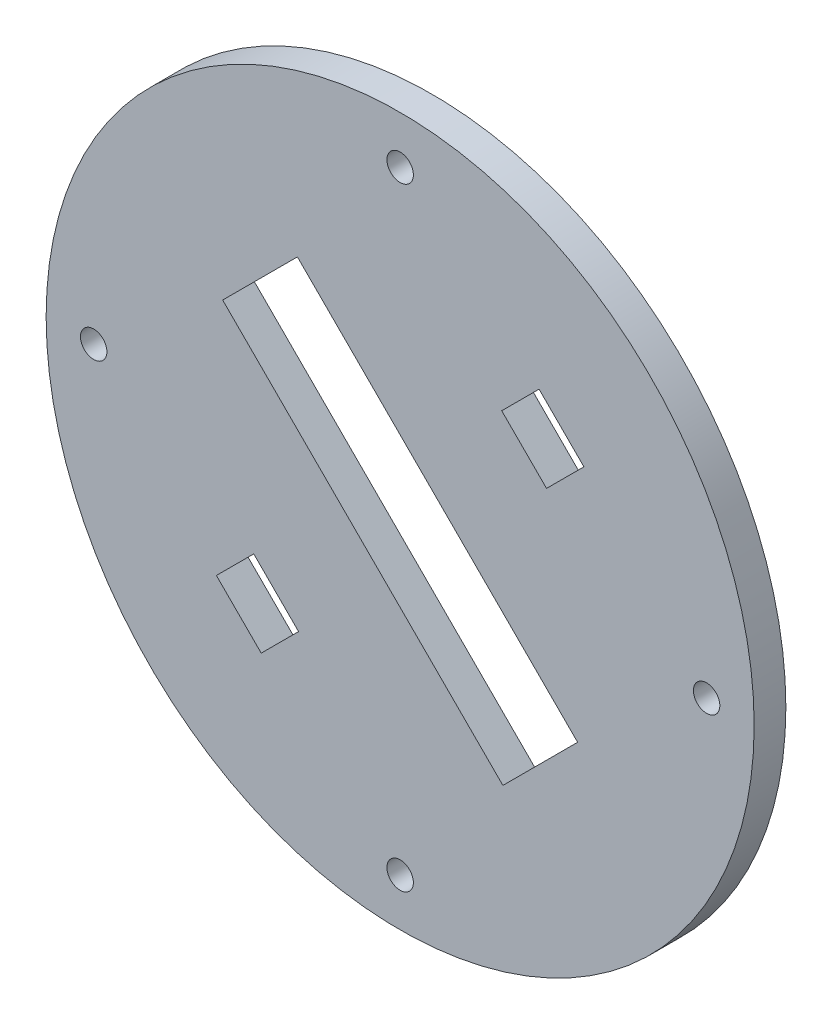
SolidWorks part; units mm, degrees
ref_plane "Front Plane" through (0, 0, 0) normal (0, 0, 1) x (1, 0, 0)
ref_plane "Top Plane" through (0, 0, 0) normal (0, 1, 0) x (1, 0, 0)
ref_plane "Right Plane" through (0, 0, 0) normal (1, 0, 0) x (0, 0, -1)
sketch "Sketch1" plane through (0, 0, 0) normal (0, 0, 1) x (1, 0, 0)
  circle A0 centre (0, 0) radius 67
  circle A1 centre (0, 58) radius 2.5
  circle A2 centre (58, 0) radius 2.5
  circle A3 centre (0, -58) radius 2.5
  circle A4 centre (-58, 0) radius 2.5
  point P14 (0, 0)
  dimension "D1" = 4
  dimension "D2" = 58
extrude "Boss-Extrude1" add sketch "Sketch1" along normal blind 6
sketch "Sketch2" plane through (0, 0, 6) normal (0, 0, 1) x (1, 0, 0)
  circle A0 centre (-42.4264, -42.4264) radius 1.5
  circle A1 centre (42.4264, 42.4264) radius 1.5
  circle A2 centre (-38.8909, 38.8909) radius 1.5
  circle A3 centre (38.8909, -38.8909) radius 1.5
  point P8 (0, 0)
  point P9 (0, 0)
  point P10 (0, 0)
  dimension "D1" = 3
  dimension "D2" = 3
  dimension "D3" = 55
  dimension "D4" = 60
  dimension "D5" = 60
sketch "Sketch3" plane through (0, 0, 6) normal (0, 0, 1) x (1, 0, 0)
  line L0 (-38.8909, 38.8909) -> (38.8909, -38.8909) construction
  line L1 (-34.4246, -26.6464) -> (-27.3536, -19.5754)
  line L2 (-34.4246, -26.6464) -> (-26.6464, -34.4246)
  line L3 (-26.6464, -34.4246) -> (-19.5754, -27.3536)
  line L4 (-27.3536, -19.5754) -> (-19.5754, -27.3536)
  line L5 (-34.4246, -26.6464) -> (-19.5754, -27.3536) construction
  line L6 (-26.6464, -34.4246) -> (-27.3536, -19.5754) construction
  line L7 (34.4246, 26.6464) -> (19.5754, 27.3536) construction
  line L8 (26.6464, 34.4246) -> (27.3536, 19.5754) construction
  line L9 (19.5754, 27.3536) -> (27.3536, 19.5754)
  line L10 (34.4246, 26.6464) -> (27.3536, 19.5754)
  line L11 (26.6464, 34.4246) -> (34.4246, 26.6464)
  line L12 (26.6464, 34.4246) -> (19.5754, 27.3536)
  point P0 (-27, -27)
  point P15 (27, 27)
  dimension "D1" = 10
  dimension "D2" = 11
  dimension "D3" = 27
  dimension "D4" = 27
extrude "Cut-Extrude3" cut sketch "Sketch3" along normal blind 47 and the other way blind 25
sketch "Sketch4" plane through (0, 0, 6) normal (0, 0, 1) x (1, 0, 0)
  line L1 (-19.4454, 33.5876) -> (33.5876, -19.4454)
  line L2 (-19.4454, 33.5876) -> (-33.5876, 19.4454)
  line L3 (-33.5876, 19.4454) -> (19.4454, -33.5876)
  line L4 (33.5876, -19.4454) -> (19.4454, -33.5876)
  line L5 (-19.4454, 33.5876) -> (19.4454, -33.5876) construction
  line L6 (-33.5876, 19.4454) -> (33.5876, -19.4454) construction
  point P0 (0, 0)
  dimension "D1" = 75
  dimension "D2" = 20
extrude "Cut-Extrude6" cut sketch "Sketch4" against normal blind 10 contours L2 L3 L4 L1
sketch "Sketch5" plane through (0, 0, 6) normal (0, 0, 1) x (1, 0, 0)
  line L0 (-34.4246, -26.6464) -> (-34.7782, -26.2929)
  line L1 (-27.3536, -19.5754) -> (-27.7071, -19.2218)
  line L2 (-27.7071, -19.2218) -> (-34.7782, -26.2929)
  line L3 (-26.6464, -34.4246) -> (-26.2929, -34.7782)
  line L6 (0, 0) -> (-38.8909, 38.8909) construction
  line L7 (-38.8909, 38.8909) -> (38.8909, -38.8909) construction
  line L8 (-34.4246, -26.6464) -> (-27.3536, -19.5754)
  line L9 (-26.6464, -34.4246) -> (-19.5754, -27.3536)
  line L18 (-26.2929, -34.7782) -> (-19.2218, -27.7071)
  line L19 (-19.2218, -27.7071) -> (-19.5754, -27.3536)
  line L20 (27.7071, 19.2218) -> (27.3536, 19.5754)
  line L21 (34.7782, 26.2929) -> (27.7071, 19.2218)
  line L22 (34.4246, 26.6464) -> (27.3536, 19.5754)
  line L23 (26.6464, 34.4246) -> (19.5754, 27.3536)
  line L24 (34.4246, 26.6464) -> (34.7782, 26.2929)
  line L25 (19.2218, 27.7071) -> (26.2929, 34.7782)
  line L26 (19.5754, 27.3536) -> (19.2218, 27.7071)
  line L27 (26.6464, 34.4246) -> (26.2929, 34.7782)
  dimension "D1" = 0.5
  dimension "D3" = 0.5
extrude "Cut-Extrude7" cut sketch "Sketch5" against normal blind 10
sketch "Sketch6" plane through (0, 0, 6) normal (0, 0, 1) x (1, 0, 0)
  line L0 (-38.8909, 38.8909) -> (38.8909, -38.8909) construction
  circle A0 centre (-27, -27) radius 5
  circle A1 centre (27, 27) radius 5
